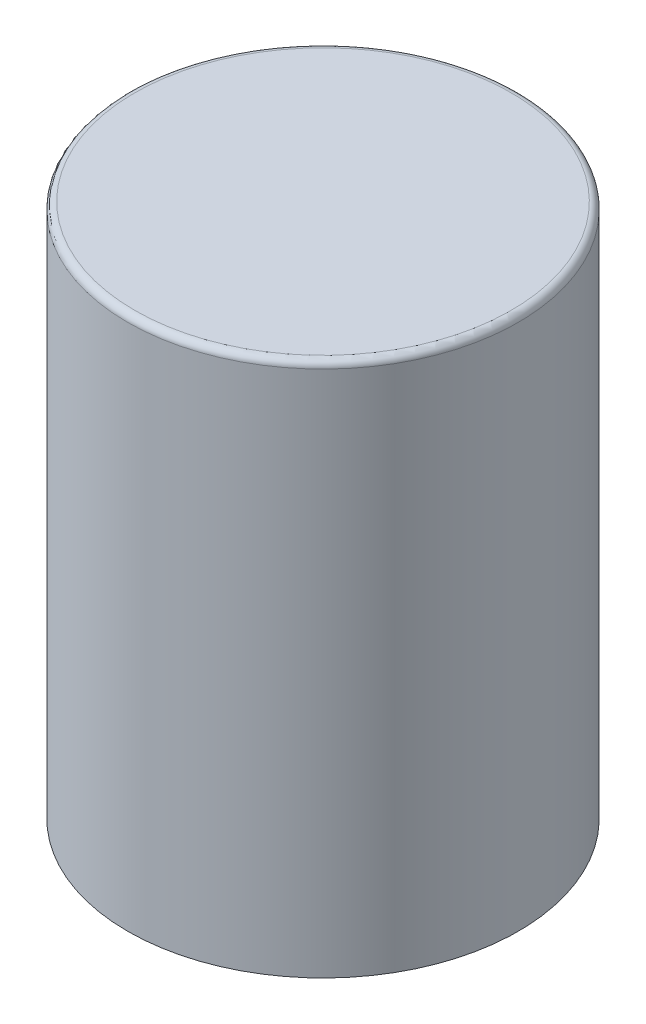
SolidWorks part; units mm, degrees
ref_plane "Front Plane" through (0, 0, 0) normal (0, 0, 1) x (1, 0, 0)
ref_plane "Top Plane" through (0, 0, 0) normal (0, 1, 0) x (1, 0, 0)
ref_plane "Right Plane" through (0, 0, 0) normal (1, 0, 0) x (0, 0, -1)
sketch "Sketch1" plane through (0, 0, 0) normal (0, 0, 1) x (1, 0, 0)
  line L0 (127, 271.5) -> (635, 271.5) construction
  line L1 (543.0904, 122.8029) -> (571.0904, 122.8029)
  line L2 (543.0904, 122.8029) -> (543.0904, 45.8796)
  line L3 (543.0904, 45.8796) -> (546.2516, 44.0963)
  line L4 (546.2516, 44.0963) -> (552.2499, 43.2047)
  line L5 (552.2499, 43.2047) -> (571.0904, 43.2047)
  line L6 (571.0904, 122.8029) -> (571.0904, 43.2047) construction
  line L7 (571.0904, 122.8029) -> (571.0904, 43.2047)
revolve "Revolve1" add sketch "Sketch1" angle 360 about L7
sketch "Sketch2" plane through (0, 43.2047, 0) normal (0, -1, 0) x (-1, 0, 0)
  circle A0 centre (-571.0904, 0) radius 29.716
extrude "Cut-Extrude1" cut sketch "Sketch2" against normal blind 3
fillet "Fillet1" radius 1 1 edges at (571.0904, 122.8029, 28)
